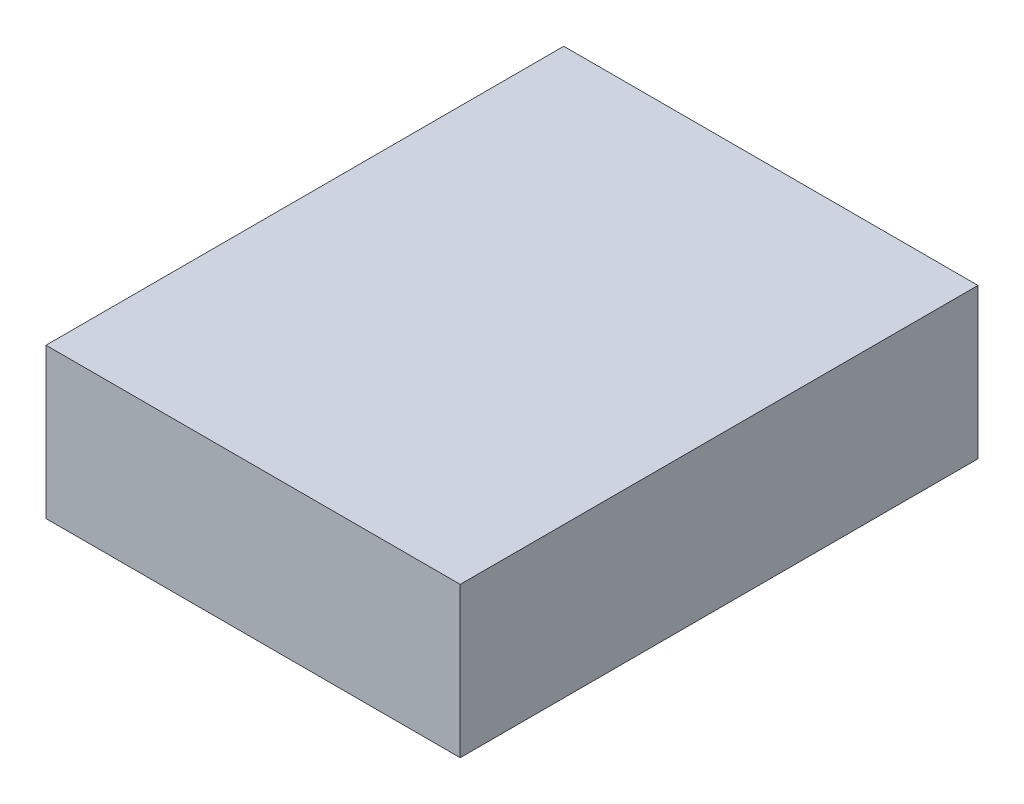
SolidWorks part; units mm, degrees
ref_plane "Front Plane" through (0, 0, 0) normal (0, 0, 1) x (1, 0, 0)
ref_plane "Top Plane" through (0, 0, 0) normal (0, 1, 0) x (1, 0, 0)
ref_plane "Right Plane" through (0, 0, 0) normal (1, 0, 0) x (0, 0, -1)
sketch "Sketch1" plane through (0, 0, 0) normal (0, 1, 0) x (1, 0, 0)
  line L1 (-40, 50) -> (40, 50)
  line L2 (-40, 50) -> (-40, -50)
  line L3 (-40, -50) -> (40, -50)
  line L4 (40, 50) -> (40, -50)
  line L5 (-40, 50) -> (40, -50) construction
  line L6 (-40, -50) -> (40, 50) construction
  point P0 (0, 0)
  dimension "D1" = 100
  dimension "D2" = 80
extrude "Boss-Extrude1" add sketch "Sketch1" along normal blind 29
